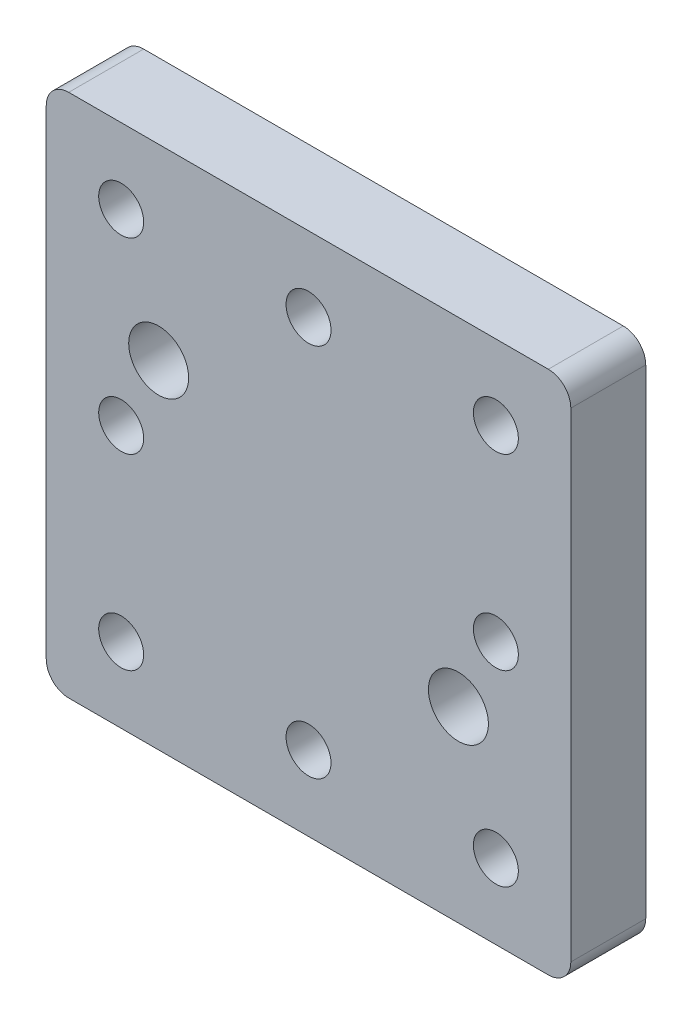
SolidWorks part; units mm, degrees
ref_plane "Front Plane" through (0, 0, 0) normal (0, 0, 1) x (1, 0, 0)
ref_plane "Top Plane" through (0, 0, 0) normal (0, 1, 0) x (1, 0, 0)
ref_plane "Right Plane" through (0, 0, 0) normal (1, 0, 0) x (0, 0, -1)
sketch "Sketch1" plane through (0, 0, 0) normal (0, 0, 1) x (1, 0, 0)
  line L1 (-35, -35) -> (35, -35)
  line L2 (-35, -35) -> (-35, 35)
  line L3 (-35, 35) -> (35, 35)
  line L4 (35, -35) -> (35, 35)
  line L5 (0, 35) -> (0, -35) construction
  line L6 (-35, 0) -> (35, 0) construction
  point P0 (0, 0)
  dimension "D1" = 70
  dimension "D2" = 70
extrude "Boss-Extrude1" add sketch "Sketch1" along normal blind 10
sketch "Sketch2" plane through (0, 0, 10) normal (0, 0, 1) x (1, 0, 0)
  circle A5 centre (-25, -25) radius 3
  circle A9 centre (25, 25) radius 3
  circle A10 centre (25, 0) radius 3
  circle A11 centre (25, -25) radius 3
  circle A12 centre (0, -25) radius 3
  circle A13 centre (-25, -25) radius 3
  circle A14 centre (-25, 0) radius 3
  circle A15 centre (-25, 25) radius 3
  circle A16 centre (0, 25) radius 3
  point P0 (0, 0)
  point P12 (0, 0)
  dimension "D3" = 50
  dimension "D4" = 50
extrude "Cut-Extrude1" cut sketch "Sketch2" against normal blind 10 contours A16 | A9 | A10 | A14 | A15 | A5 | A12 | A11
sketch "Sketch3" plane through (0, 0, 0) normal (0, 0, -1) x (-1, 0, 0)
  line L5 (-15, -15) -> (15, -15)
  line L6 (-15, -15) -> (-15, 15)
  line L7 (-15, 15) -> (15, 15)
  line L8 (15, -15) -> (15, 15)
  line L9 (0, 15) -> (0, -15) construction
  line L10 (-15, 0) -> (15, 0) construction
  line L15 (0, 20) -> (0, -20) construction
  line L16 (-20, 0) -> (20, 0) construction
  circle A0 centre (-20, -10) radius 4
  circle A1 centre (20, 10) radius 4
  point P0 (0, 0)
  point P4 (0, 0)
  dimension "D5" = 10
  dimension "D1" = 30
  dimension "D2" = 30
  dimension "D6" = 10
fillet "Fillet1" radius 3 4 edges at (-35, -35, 5) (35, -35, 5) (35, 35, 5) (-35, 35, 5)
extrude "Cut-Extrude2" cut sketch "Sketch3" against normal blind 10 contours A1 | A0
